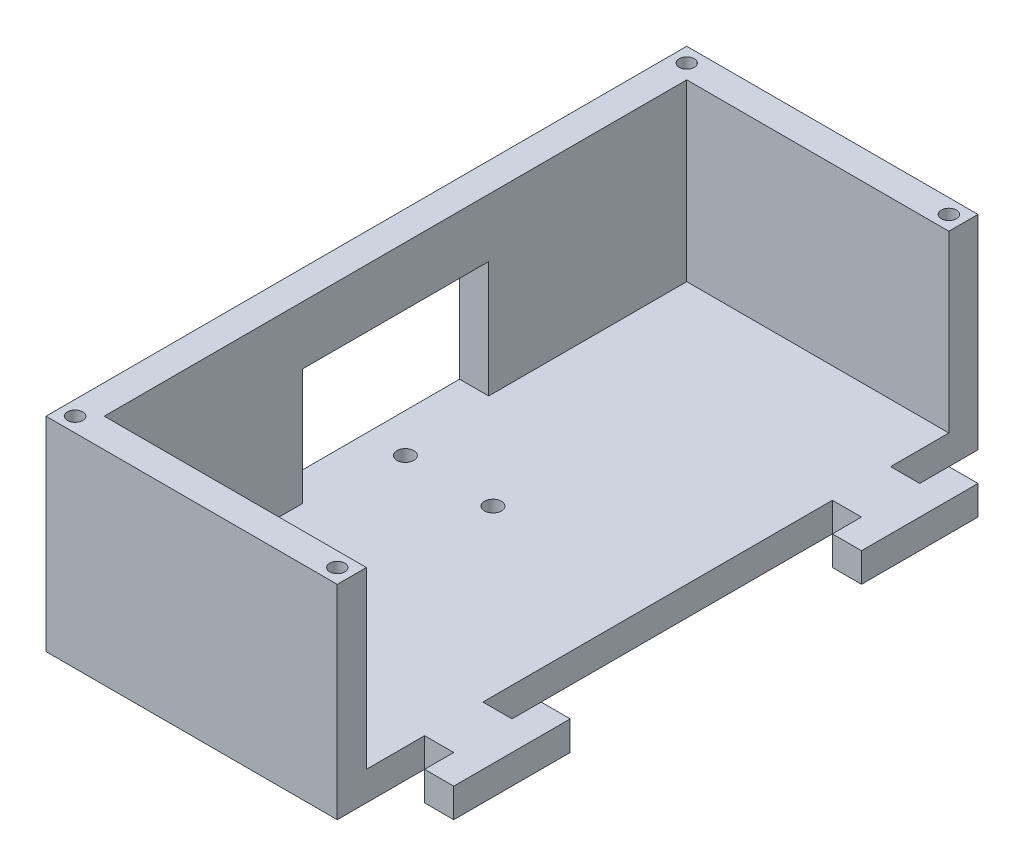
SolidWorks part; units mm, degrees
ref_plane "Front Plane" through (0, 0, 0) normal (0, 0, 1) x (1, 0, 0)
ref_plane "Top Plane" through (0, 0, 0) normal (0, 1, 0) x (1, 0, 0)
ref_plane "Right Plane" through (0, 0, 0) normal (1, 0, 0) x (0, 0, -1)
sketch "Sketch1" plane through (0, 0, 0) normal (0, 1, 0) x (1, 0, 0)
  line L1 (-38.1, -69.85) -> (25.4, -69.85)
  line L2 (-38.1, -69.85) -> (-38.1, 69.85)
  line L3 (-38.1, 69.85) -> (25.4, 69.85)
  line L4 (25.4, -69.85) -> (25.4, 69.85)
  line L5 (-38.1, -69.85) -> (25.4, 69.85) construction
  line L6 (-38.1, 69.85) -> (25.4, -69.85) construction
  point P0 (-6.35, 0)
  dimension "D1" = 63.5
  dimension "D2" = 139.7
  dimension "D3" = 6.35
extrude "Boss-Extrude1" add sketch "Sketch1" along normal blind 6.35
sketch "Sketch3" plane through (0, 6.35, 0) normal (0, 1, 0) x (1, 0, 0)
  line L0 (25.4, -69.85) -> (25.4, 69.85) construction
  line L1 (-38.1, 69.85) -> (25.4, 69.85)
  line L2 (-38.1, 69.85) -> (-38.1, 63.5)
  line L3 (-38.1, 63.5) -> (25.4, 63.5)
  line L4 (25.4, 69.85) -> (25.4, 63.5)
  line L6 (-38.1, -69.85) -> (25.4, -69.85)
  line L7 (-38.1, -69.85) -> (-38.1, -63.5)
  line L8 (-38.1, -63.5) -> (25.4, -63.5)
  line L9 (25.4, -69.85) -> (25.4, -63.5)
  dimension "D1" = 6.35
extrude "Boss-Extrude2" add sketch "Sketch3" along normal blind 38.1
sketch "Sketch6" plane through (0, 6.35, 0) normal (0, 1, 0) x (1, 0, 0)
  line L0 (25.4, -63.5) -> (25.4, 63.5) construction
  line L1 (25.4, 50.8) -> (31.75, 50.8)
  line L2 (25.4, 50.8) -> (25.4, 38.1)
  line L3 (25.4, 38.1) -> (31.75, 38.1)
  line L5 (25.4, 69.85) -> (-38.1, 69.85) construction
  line L6 (31.75, 57.15) -> (38.1, 57.15)
  line L7 (31.75, 57.15) -> (31.75, 50.8)
  line L8 (31.75, 31.75) -> (38.1, 31.75)
  line L9 (38.1, 57.15) -> (38.1, 31.75)
  line L10 (31.75, 38.1) -> (31.75, 31.75)
  point P10 (38.1, 44.45)
  point P11 (25.4, 44.45)
  dimension "D1" = 6.35
  dimension "D2" = 12.7
  dimension "D3" = 25.4
  dimension "D4" = 6.35
  dimension "D5" = 25.4
extrude "Boss-Extrude3" add sketch "Sketch6" against normal up to surface (6.35 mm away) up to face at (-6.35, 0, 0)
mirror "Mirror1" about plane through (0, 0, 0) normal (0, 0, 1) of "Boss-Extrude3"
sketch "Sketch7" plane through (0, 0, 0) normal (0, -1, 0) x (1, 0, 0)
  circle A0 centre (-10.5, 0) radius 1.85 construction
  circle A1 centre (-29.6, 0) radius 1.85 construction
  circle A2 centre (-10.5, 0) radius 1.85
  circle A3 centre (-29.6, 0) radius 1.85
extrude "Cut-Extrude1" cut sketch "Sketch7" against normal through all
sketch "Sketch8" plane through (0, 6.35, 0) normal (0, 1, 0) x (1, 0, 0)
  line L0 (-38.1, 69.85) -> (-38.1, 63.5) construction
  line L1 (-38.1, 63.5) -> (-31.75, 63.5)
  line L2 (-38.1, 63.5) -> (-38.1, 20.32)
  line L3 (-38.1, 20.32) -> (-31.75, 20.32)
  line L4 (-31.75, 63.5) -> (-31.75, 20.32)
  line L5 (-38.1, -63.5) -> (-31.75, -63.5)
  line L6 (-38.1, -63.5) -> (-38.1, -20.32)
  line L7 (-38.1, -20.32) -> (-31.75, -20.32)
  line L8 (-31.75, -63.5) -> (-31.75, -20.32)
  dimension "D1" = 40.64
extrude "Boss-Extrude4" add sketch "Sketch8" along normal up to surface (38.1 mm away) up to face at (-6.35, 44.45, 66.675)
sketch "Sketch9" plane through (-38.1, 0, 0) normal (-1, 0, 0) x (0, 0, 1)
  line L0 (20.32, 44.45) -> (20.32, 6.35) construction
  line L1 (-20.32, 44.45) -> (20.32, 44.45)
  line L2 (-20.32, 44.45) -> (-20.32, 31.75)
  line L3 (-20.32, 31.75) -> (20.32, 31.75)
  line L4 (20.32, 44.45) -> (20.32, 31.75)
  line L5 (-20.32, 6.35) -> (20.32, 6.35) construction
  dimension "D1" = 25.4
extrude "Boss-Extrude5" add sketch "Sketch9" against normal up to surface (6.35 mm away) up to face at (-31.75, 25.4, 41.91)
sketch "Sketch10" plane through (0, 44.45, 0) normal (0, 1, 0) x (1, 0, 0)
  line L0 (-38.1, 69.85) -> (-31.75, 63.5) construction
  circle A0 centre (-34.925, 66.675) radius 1.65
  point P6 (0, 0)
  point P7 (-34.925, 66.675)
  dimension "D1" = 3.3
extrude "Cut-Extrude2" cut sketch "Sketch10" against normal blind 12
ref_plane "Plane1" through (-6.35, 0, 0) normal (-1, 0, 0) x (0, 0, 1)
mirror "Mirror2" about plane through (-6.35, 0, 0) normal (-1, 0, 0) of "Cut-Extrude2" second plane through (0, 0, 0) second plane normal (0, 0, 1)
